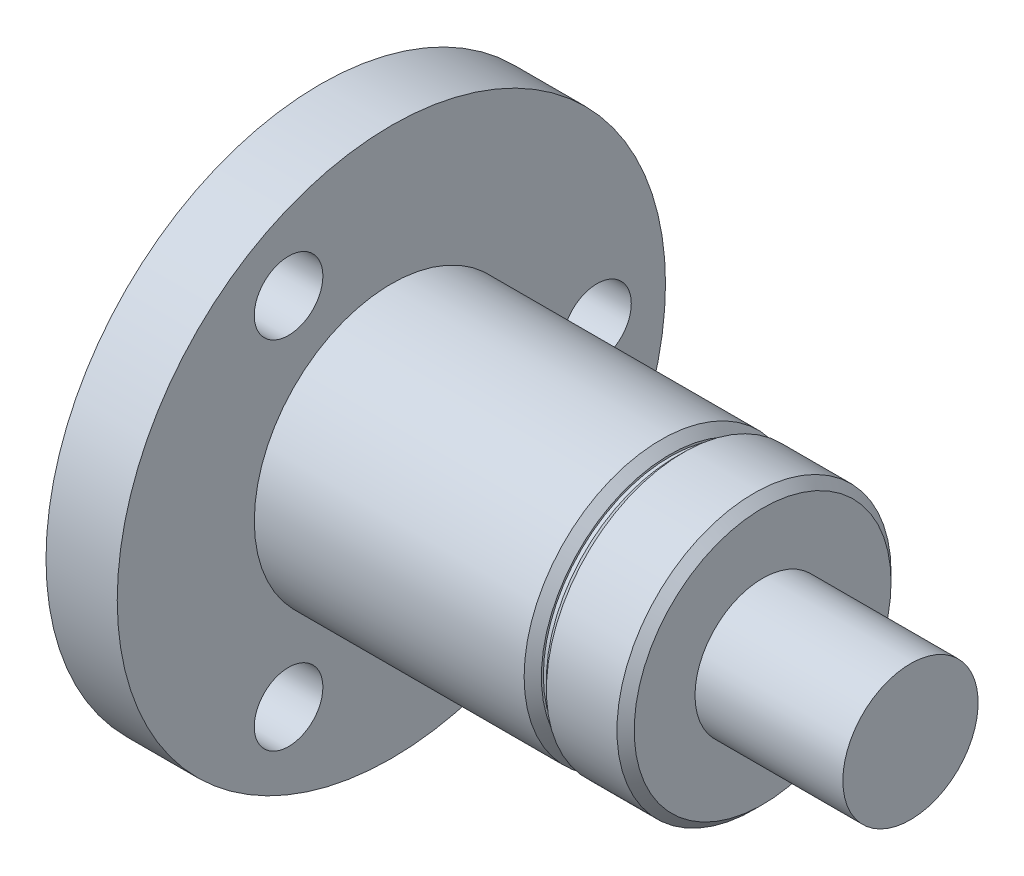
SolidWorks part; units mm, degrees
ref_plane "Front Plane" through (0, 0, 0) normal (0, 0, 1) x (1, 0, 0)
ref_plane "Top Plane" through (0, 0, 0) normal (0, 1, 0) x (1, 0, 0)
ref_plane "Right Plane" through (0, 0, 0) normal (1, 0, 0) x (0, 0, -1)
sketch "Sketch1" plane through (0, 0, 0) normal (0, 0, 1) x (1, 0, 0)
  line L1 (17.2, 6.35) -> (17.2, 0)
  line L2 (0, 6.35) -> (0, 12.7)
  line L3 (0, 12.7) -> (-3.3, 12.7)
  line L4 (-3.3, 12.7) -> (-3.3, 0)
  line L5 (-3.3, 0) -> (17.2, 0)
  line L6 (-9.6, 3.1336) -> (-9.6, 0)
  line L7 (-9.6, 3.1336) -> (24.05, 3.1336)
  line L8 (24.05, 0) -> (24.05, 3.1336)
  line L9 (-9.6, 0) -> (24.05, 0)
  line L10 (0, 6.35) -> (12.9, 6.35)
  line L11 (12.9, 6.35) -> (12.9, 5.8595)
  line L12 (12.9, 5.8595) -> (13.1322, 5.8595)
  line L13 (13.1322, 5.8595) -> (13.1322, 6.35)
  line L14 (13.1322, 6.35) -> (17.2, 6.35)
  dimension "D1" = 3.3
  dimension "D2" = 12.9
  dimension "D3" = 6.35
  dimension "D4" = 12.7
  dimension "D5" = 0
  dimension "D6" = 0
  dimension "D7" = 6.3
  dimension "D8" = 33.65
  dimension "D9" = 20.5
  dimension "D10" = 0
revolve "Revolve1" add sketch "Sketch1" angle 360 about L5
sketch "Sketch2" plane through (0, 0, 0) normal (1, 0, 0) x (0, 0, -1)
  circle A0 centre (9.525, 0) radius 1.59
  dimension "D1" = 3.18
  dimension "D2" = 9.525
extrude "Cut-Extrude1" cut sketch "Sketch2" against normal blind 10
pattern_circular "CirPattern1" count 3 over 360 about axis through (0, 0, 0) along (1, 0, 0) of "Cut-Extrude1"
chamfer "Chamfer1" distance 0.4 angle 45 3 edges at (17.2, 0, 6.35) (13.1322, 0, 6.35) (12.9, 0, 6.35)
